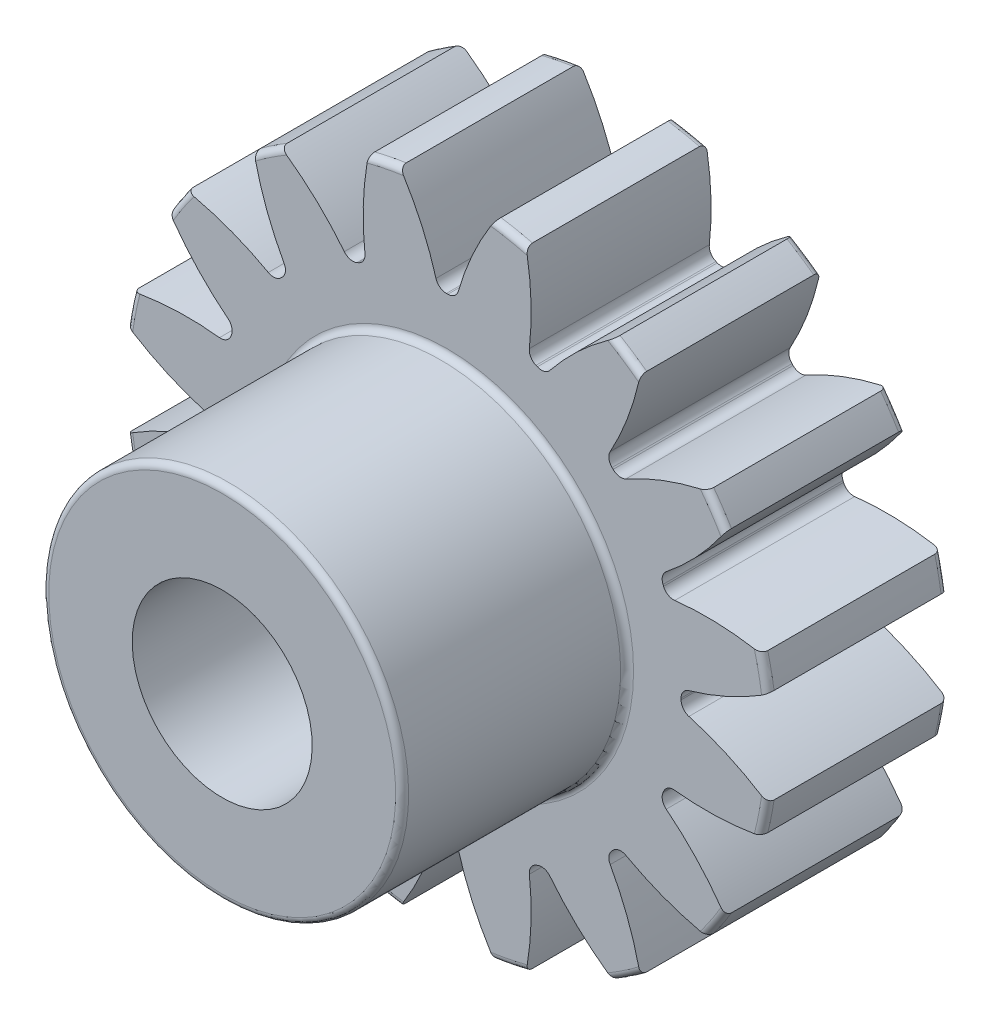
SolidWorks part; units mm, degrees
material "POM Acetal Copolymer"
ref_plane "Front Plane" through (0, 0, 0) normal (0, 0, 1) x (1, 0, 0)
ref_plane "Top Plane" through (0, 0, 0) normal (0, 1, 0) x (1, 0, 0)
ref_plane "Right Plane" through (0, 0, 0) normal (1, 0, 0) x (0, 0, -1)
sketch "Sketch1" plane through (0, 0, 0) normal (0, 0, 1) x (1, 0, 0)
  line L0 (-203.2, 0) -> (203.2, 0) construction
  circle A0 centre (0, 0) radius 7.2 construction
  circle A1 centre (0, 0) radius 6.4 construction
  circle A2 centre (0, 0) radius 5.2 construction
  circle A3 centre (0, 0) radius 4 construction
  circle A4 centre (0, 0) radius 2 construction
  dimension "D2" = 0.8
  dimension "D3" = 2
  dimension "D1" = 2
sketch "Sketch2" plane through (0, 0, 0) normal (1, 0, 0) x (0, 0, -1)
  line L0 (0, 0) -> (-4, 0) construction
  line L1 (-4, 0) -> (-9, 0) construction
  dimension "Overall Width" = 9
  dimension "Face Width" = 4
sketch "Sketch4" plane through (0, 0, 0) normal (1, 0, 0) x (0, 0, -1)
  line L0 (-9, 2) -> (-9, 4)
  line L1 (-9, 4) -> (-4, 4)
  line L2 (-4, 4) -> (-4, 7.2)
  line L3 (-4, 7.2) -> (0, 7.2)
  line L4 (0, 7.2) -> (0, 2)
  line L5 (-4, 4) -> (-4, 0) construction
  line L6 (0, 7.2) -> (0, -7.2) construction
  line L7 (-4, 4) -> (0, 4) construction
  line L12 (-9, 2) -> (0, 2)
revolve "Revolve1" add sketch "Sketch4" angle 360 about L1
fillet "Fillet2" radius 0.144 4 edges at (0, 4, 9) (0, 4, 4) (0, 7.2, 4) (0, 7.2, 0)
sketch "Sketch7" plane through (0, 0, 4) normal (0, 0, 1) x (1, 0, 0)
  line L0 (0, 0) -> (0, 7.2) construction
  line L1 (0.6273, 6.3692) -> (0.9928, 7.1312) construction
  line L3 (1.4046, 7.0617) -> (1.2486, 6.277) construction
  line L4 (1.2486, 6.277) -> (1.0145, 5.1001) construction
  line L5 (0, 0) -> (1.0145, 5.1001) construction
  line L6 (0.6273, 6.3692) -> (0, 0) construction
  line L7 (0.6273, 6.3692) -> (0.7057, 7.1653) construction
  line L8 (0.6273, 6.3692) -> (0, 0) construction
  circle A0 centre (0, 0) radius 7.2 construction
  arc A1 (-0.0167, 5.2) -> (0.0167, 5.2) centre (0, 0) cw
  circle A2 centre (0, 0) radius 5.2 construction
  arc A3 (-0.6273, 6.3692) -> (0.6273, 6.3692) centre (0, 0) cw construction
  circle A4 centre (0, 0) radius 6.4 construction
  arc A5 (1.7523, 6.9835) -> (1.0536, 7.1225) centre (0, 0) ccw construction
  arc A6 (0.6273, 6.3692) -> (1.8578, 6.1244) centre (0, 0) cw construction
  arc A7 (-1.0536, 7.1225) -> (1.0536, 7.1225) centre (0, 0) cw
  arc A8 (0.2481, 5.3735) -> (1.0536, 7.1225) centre (6.3978, 3.6013) cw
  arc A9 (-0.2481, 5.3735) -> (-1.0536, 7.1225) centre (-6.3978, 3.6013) ccw
  arc A10 (-0.0167, 5.2) -> (-0.2481, 5.3735) centre (-0.0175, 5.44) cw
  arc A11 (0.0167, 5.2) -> (0.2481, 5.3735) centre (0.0175, 5.44) ccw
  point P26 (-0.1997, 5.1962)
  point P29 (0.1997, 5.1962)
  dimension "D4" = 0.24
  dimension "D5" = 6.4
  dimension "D3" = 20
  dimension "D1" = 2.5133
  dimension "D2" = 1.2566
extrude "Cut-Extrude2" cut sketch "Sketch7" against normal through all
pattern_circular "CirPattern1" count 16 over 360 about axis through (0, 0, 0) along (0, 0, 1) of "Cut-Extrude2"
equation "\"D1@Sketch1\"=2.5*(\"Pitch Dia.@Sketch1\"/\"Number of Teeth@Sketch1\")"
equation "\"D1@CirPattern1\"=\"Number of Teeth@Sketch1\""
equation "\"D1@Fillet2\"=\"OD@Sketch1\"*.01"
equation "\"D1@Sketch7\"=3.14159*(\"Pitch Dia.@Sketch1\"/\"Number of Teeth@Sketch1\")"
equation "\"D2@Sketch7\"=\"D1@Sketch7\"/2"
equation "\"D4@Sketch7\"=\"D1@Sketch7\"*.0955"
equation "\"D5@Sketch7\"=\"Pitch Dia.@Sketch1\"/2"
